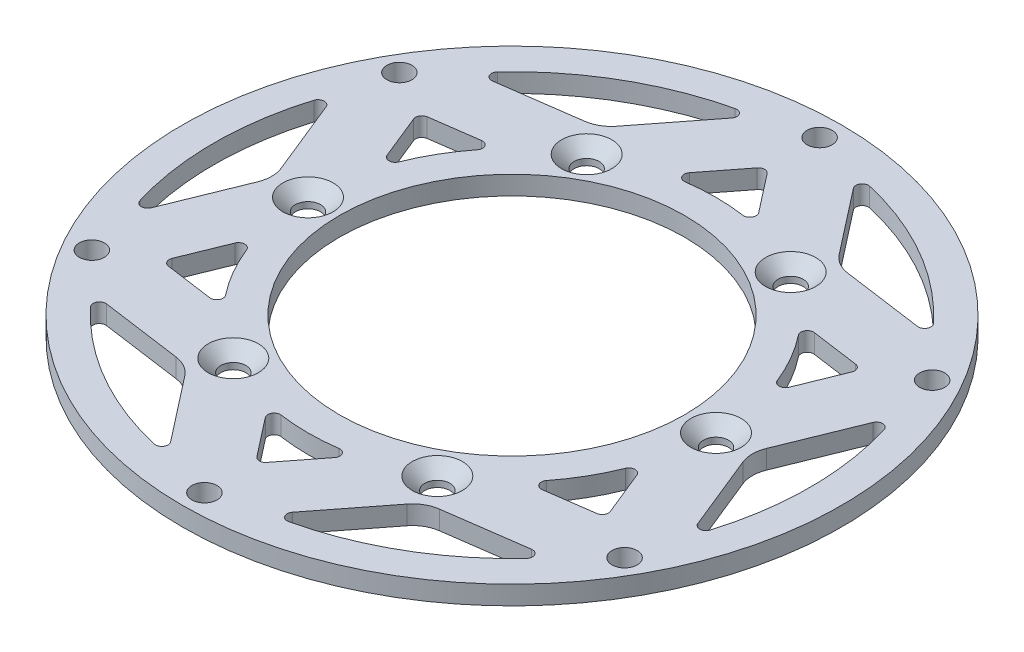
SolidWorks part; units mm, degrees
material "Thornel Mat VMA"
ref_plane "前视基准面" through (0, 0, 0) normal (0, 0, 1) x (1, 0, 0)
ref_plane "上视基准面" through (0, 0, 0) normal (0, 1, 0) x (1, 0, 0)
ref_plane "右视基准面" through (0, 0, 0) normal (1, 0, 0) x (0, 0, -1)
sketch "草图1" plane through (0, 0, 0) normal (0, 1, 0) x (1, 0, 0)
  circle A0 centre (0, 0) radius 52.5
  circle A1 centre (0, 0) radius 49 construction
  circle A2 centre (0, 0) radius 32.5 construction
  circle A3 centre (0, 49) radius 2
  circle A4 centre (-16.25, 28.1458) radius 2
  circle A5 centre (42.4352, 24.5) radius 2
  circle A6 centre (16.25, 28.1458) radius 2
  circle A7 centre (42.4352, -24.5) radius 2
  circle A8 centre (32.5, 0) radius 2
  circle A9 centre (0, -49) radius 2
  circle A10 centre (16.25, -28.1458) radius 2
  circle A11 centre (-42.4352, -24.5) radius 2
  circle A12 centre (-16.25, -28.1458) radius 2
  circle A13 centre (-42.4352, 24.5) radius 2
  circle A14 centre (-32.5, 0) radius 2
  circle A15 centre (0, 0) radius 27.5
  point P9 (16.25, 28.1458)
  point P31 (6.7138, 26.2106)
  dimension "D1" = 105
  dimension "D2" = 65
  dimension "D3" = 3.5
  dimension "D4" = 4
  dimension "D5" = 4
  dimension "D7" = 55
  dimension "D6" = 6
extrude "凸台-拉伸1" add sketch "草图1" along normal blind 3
hole_wizard "孔1" positions "草图2" profile "草图3" legacy end condition through all
sketch "草图2" plane through (0, 3, 0) normal (0, 1, 0) x (1, 0, 0)
  point P0 (-16.25, 28.1458)
  point P7 (16.25, 28.1458)
  point P8 (32.5, 0)
  point P9 (16.25, -28.1458)
  point P10 (-16.25, -28.1458)
  point P11 (-32.5, 0)
  point P12 (16.25, 28.1458)
  dimension "D1" = 6
sketch "草图3" plane through (-16.25, 3, -28.1458) normal (1, 0, 0) x (0, 0, 1)
  line L0 (0, 0) -> (0, 3)
  line L1 (0, 3) -> (2, 3)
  line L2 (2, 3) -> (2, 2)
  line L3 (2, 2) -> (4, 0)
  line L4 (4, 0) -> (0, 0)
  line L5 (0, -6.4453) -> (0, 115.525) construction
  line L6 (-2, 2) -> (-4, 0) construction
  dimension "直径" = 4
  dimension "深度" = 3
  dimension "锥坑角度" = 90
  dimension "锥坑直径" = 8
sketch "草图5" plane through (0, 3, 0) normal (0, 1, 0) x (1, 0, 0)
  line L0 (0, 49) -> (-16.25, 28.1458) construction
  line L1 (-16.25, 28.1458) -> (-42.4352, 24.5) construction
  line L2 (0, 49) -> (16.25, 28.1458) construction
  line L3 (-8.0419, 46.8143) -> (-18.9477, 32.8184)
  line L4 (-18.9477, 32.8184) -> (-36.5214, 30.3716)
  line L5 (0, 40.8653) -> (7.1365, 31.7068)
  line L6 (0, 40.8653) -> (-7.1365, 31.7068)
  line L11 (18.9477, 32.8184) -> (8.0419, 46.8143)
  line L12 (36.5214, 30.3716) -> (18.9477, 32.8184)
  line L13 (35.3904, 20.4326) -> (23.8906, 22.0338)
  line L14 (35.3904, 20.4326) -> (31.0271, 9.673)
  line L15 (37.8955, 0) -> (44.5633, 16.4427)
  line L16 (44.5633, -16.4427) -> (37.8955, 0)
  line L17 (35.3904, -20.4326) -> (31.0271, -9.673)
  line L18 (35.3904, -20.4326) -> (23.8906, -22.0338)
  line L19 (18.9477, -32.8184) -> (36.5214, -30.3716)
  line L20 (8.0419, -46.8143) -> (18.9477, -32.8184)
  line L21 (0, -40.8653) -> (7.1365, -31.7068)
  line L22 (0, -40.8653) -> (-7.1365, -31.7068)
  line L23 (-18.9477, -32.8184) -> (-8.0419, -46.8143)
  line L24 (-36.5214, -30.3716) -> (-18.9477, -32.8184)
  line L25 (-35.3904, -20.4326) -> (-23.8906, -22.0338)
  line L26 (-35.3904, -20.4326) -> (-31.0271, -9.673)
  line L27 (-37.8955, 0) -> (-44.5633, -16.4427)
  line L28 (-44.5633, 16.4427) -> (-37.8955, 0)
  line L29 (-35.3904, 20.4326) -> (-31.0271, 9.673)
  line L30 (-35.3904, 20.4326) -> (-23.8906, 22.0338)
  circle A0 centre (0, 0) radius 27.5 construction
  arc A1 (-8.0419, 46.8143) -> (-36.5214, 30.3716) centre (0, 0) ccw
  circle A2 centre (0, 0) radius 52.5 construction
  arc A3 (7.1365, 31.7068) -> (-7.1365, 31.7068) centre (0, 0) ccw
  arc A5 (36.5214, 30.3716) -> (8.0419, 46.8143) centre (0, 0) ccw
  arc A6 (31.0271, 9.673) -> (23.8906, 22.0338) centre (0, 0) ccw
  arc A7 (44.5633, -16.4427) -> (44.5633, 16.4427) centre (0, 0) ccw
  arc A8 (23.8906, -22.0338) -> (31.0271, -9.673) centre (0, 0) ccw
  arc A9 (8.0419, -46.8143) -> (36.5214, -30.3716) centre (0, 0) ccw
  arc A10 (-7.1365, -31.7068) -> (7.1365, -31.7068) centre (0, 0) ccw
  arc A11 (-36.5214, -30.3716) -> (-8.0419, -46.8143) centre (0, 0) ccw
  arc A12 (-31.0271, -9.673) -> (-23.8906, -22.0338) centre (0, 0) ccw
  arc A13 (-44.5633, 16.4427) -> (-44.5633, -16.4427) centre (0, 0) ccw
  arc A14 (-23.8906, 22.0338) -> (-31.0271, 9.673) centre (0, 0) ccw
  point P2 (-20.3502, 22.4476)
  point P3 (16.25, 28.1458)
  point P8 (-31.0444, 45.9104)
  point P17 (0, 0)
  point P20 (-42.4352, 24.5)
  point P21 (-18.999, 54.3038)
  point P22 (-12.4243, 13.1799)
  point P23 (-6.8922, 49.4033)
  point P25 (-12.25, 32.3703)
  point P26 (-18.2918, 32.2827)
  point P27 (-16.25, 28.1458)
  point P64 (-6.9988, 54.2311)
  point P65 (-6.3155, 40.4526)
  point P66 (0, 49)
  point P68 (-1.3308, 39.1574)
  point P69 (8.125, 35.776)
  point P70 (-4.3471, 35.2865)
  point P71 (0, 40.9227)
  point P72 (6.8529, 33.4571)
  point P73 (-33.2673, 47.7352)
  point P75 (0, 0)
  point P77 (0.7468, 28.1458)
  point P79 (8.0419, 30.8085)
  dimension "D3" = 5
  dimension "D5" = 5
  dimension "D6" = 5
  dimension "D1" = 5
  dimension "D2" = 5
  dimension "D7" = 5
  dimension "D4" = 6
extrude "切除-拉伸1" cut sketch "草图5" against normal blind 10
fillet "圆角1" radius 5 6 edges at (18.9477, 1.5, -32.8184) (37.8955, 1.5, 0) (18.9477, 1.5, 32.8184) (-18.9477, 1.5, 32.8184) (-37.8955, 1.5, 0) (-18.9477, 1.5, -32.8184)
fillet "圆角2" radius 1 30 edges at (-36.5214, 1.5, -30.3716) (-8.0419, 1.5, -46.8143) (-23.8906, 1.5, 22.0338) (-35.3904, 1.5, 20.4326) (-31.0271, 1.5, 9.673) (-44.5633, 1.5, 16.4427) (-44.5633, 1.5, -16.4427) (-31.0271, 1.5, -9.673) (-23.8906, 1.5, -22.0338) (7.1365, 1.5, -31.7068) (-7.1365, 1.5, -31.7068) (0, 1.5, -40.8653) (8.0419, 1.5, -46.8143) (36.5214, 1.5, -30.3716) (23.8906, 1.5, -22.0338) (35.3904, 1.5, -20.4326) (31.0271, 1.5, -9.673) (44.5633, 1.5, -16.4427) (44.5633, 1.5, 16.4427) (31.0271, 1.5, 9.673) (35.3904, 1.5, 20.4326) (23.8906, 1.5, 22.0338) (36.5214, 1.5, 30.3716) (8.0419, 1.5, 46.8143) (7.1365, 1.5, 31.7068) (0, 1.5, 40.8653) (-7.1365, 1.5, 31.7068) (-8.0419, 1.5, 46.8143) (-36.5214, 1.5, 30.3716) (-35.3904, 1.5, -20.4326)
